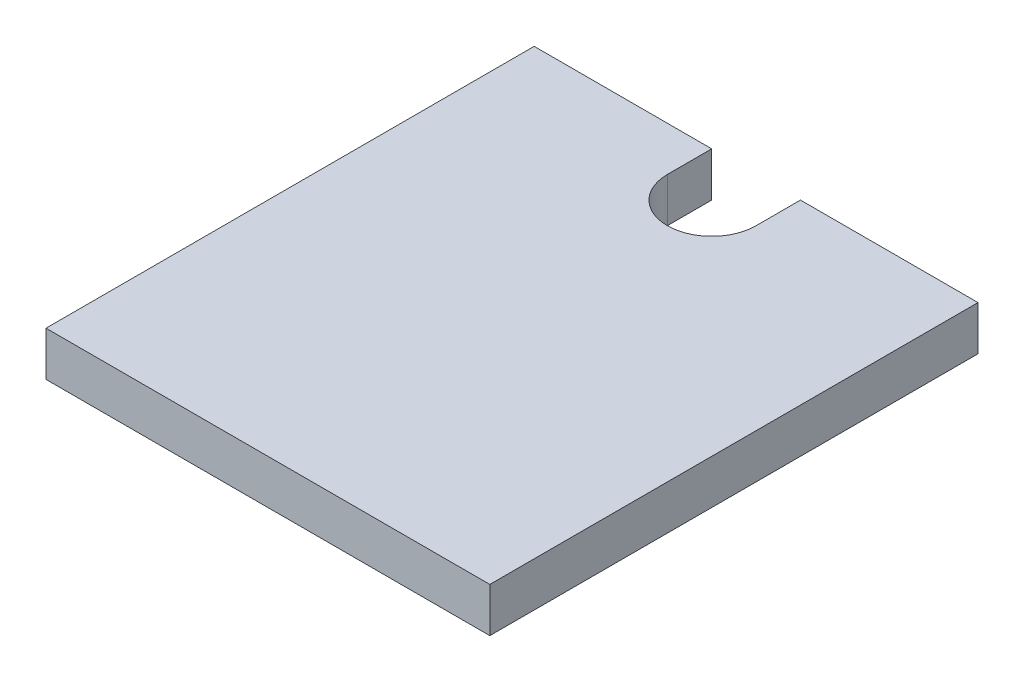
SolidWorks part; units mm, degrees
ref_plane "Front Plane" through (0, 0, 0) normal (0, 0, 1) x (1, 0, 0)
ref_plane "Top Plane" through (0, 0, 0) normal (0, 1, 0) x (1, 0, 0)
ref_plane "Right Plane" through (0, 0, 0) normal (1, 0, 0) x (0, 0, -1)
sketch "Sketch2" plane through (0, 0, 0) normal (0, 1, 0) x (1, 0, 0)
  line L1 (-25, 27.5) -> (-5, 27.5)
  line L2 (-25, 27.5) -> (-25, -27.5)
  line L3 (-25, -27.5) -> (25, -27.5)
  line L4 (25, 27.5) -> (25, -27.5)
  line L5 (-25, 27.5) -> (25, -27.5) construction
  line L6 (-25, -27.5) -> (25, 27.5) construction
  line L7 (5, 27.5) -> (25, 27.5)
  line L8 (-5, 22.5) -> (-5, 27.5)
  line L9 (5, 22.5) -> (5, 27.5)
  arc A0 (5, 22.5) -> (-5, 22.5) centre (0, 22.5) cw
  point P0 (0, 0)
  point P11 (0, 22.5)
  dimension "D1" = 50
  dimension "D2" = 55
extrude "Boss-Extrude5" add sketch "Sketch2" along normal blind 5
